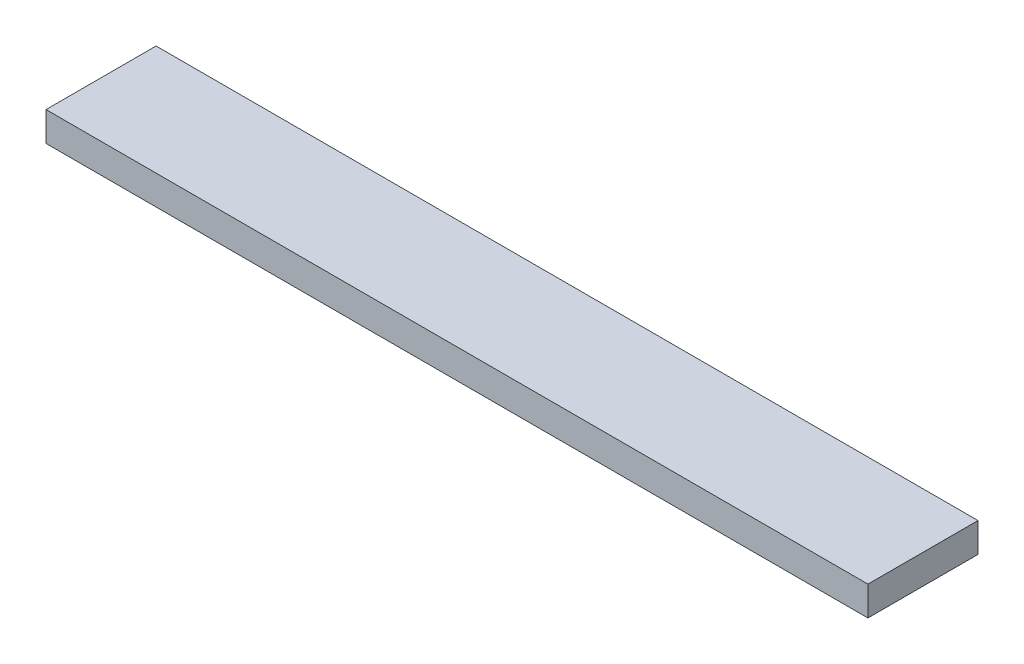
SolidWorks part; units mm, degrees
ref_plane "Front Plane" through (0, 0, 0) normal (0, 0, 1) x (1, 0, 0)
ref_plane "Top Plane" through (0, 0, 0) normal (0, 1, 0) x (1, 0, 0)
ref_plane "Right Plane" through (0, 0, 0) normal (1, 0, 0) x (0, 0, -1)
sketch "Sketch1" plane through (0, 0, 0) normal (0, 1, 0) x (1, 0, 0)
  line L1 (-56, -7.5) -> (56, -7.5)
  line L2 (-56, -7.5) -> (-56, 7.5)
  line L3 (-56, 7.5) -> (56, 7.5)
  line L4 (56, -7.5) -> (56, 7.5)
  line L5 (-56, -7.5) -> (56, 7.5) construction
  line L6 (-56, 7.5) -> (56, -7.5) construction
  point P0 (0, 0)
  dimension "D1" = 112
  dimension "D2" = 15
extrude "Boss-Extrude1" add sketch "Sketch1" along normal blind 4
